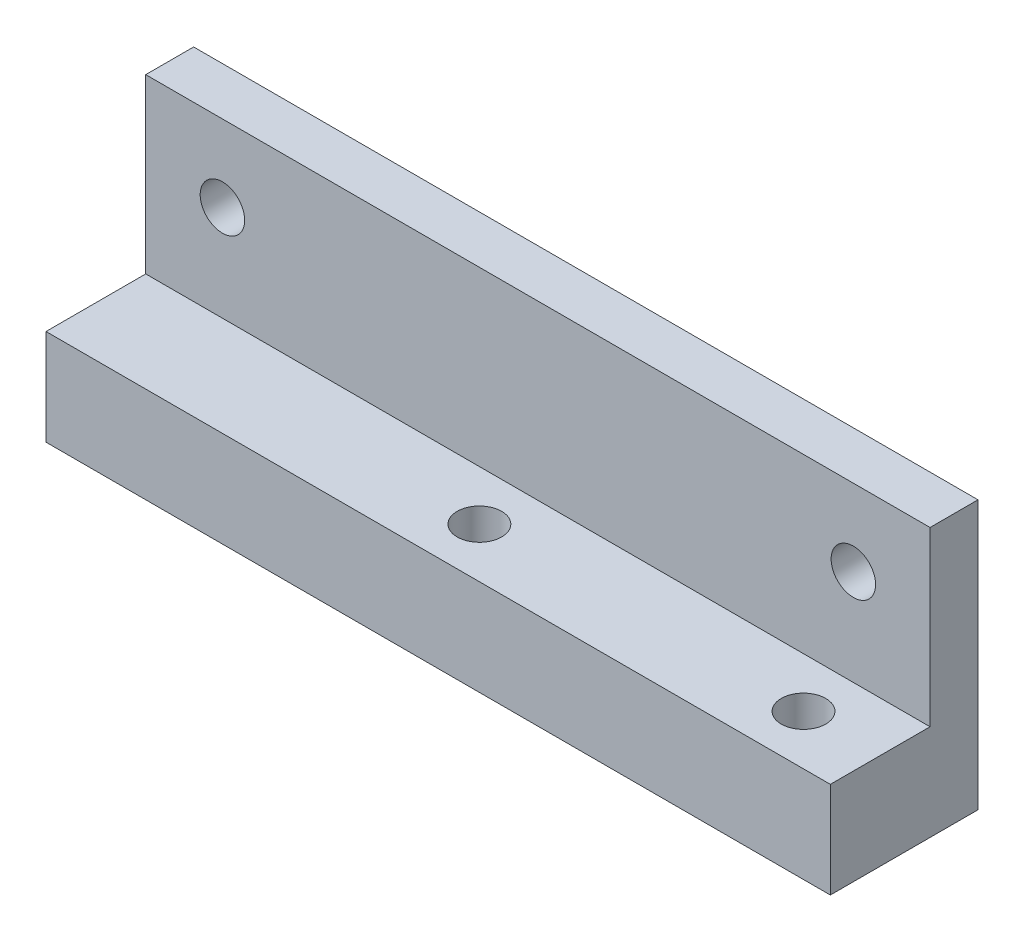
SolidWorks part; units mm, degrees
material "ABS"
ref_plane "Front Plane" through (0, 0, 0) normal (0, 0, 1) x (1, 0, 0)
ref_plane "Top Plane" through (0, 0, 0) normal (0, 1, 0) x (1, 0, 0)
ref_plane "Right Plane" through (0, 0, 0) normal (1, 0, 0) x (0, 0, -1)
sketch "Sketch1" plane through (0, 0, 0) normal (0, 1, 0) x (1, 0, 0)
  line L1 (0, 0) -> (51.943, 0)
  line L2 (0, 0) -> (0, 9.779)
  line L3 (0, 9.779) -> (51.943, 9.779)
  line L4 (51.943, 0) -> (51.943, 9.779)
  dimension "D1" = 51.943
  dimension "D2" = 9.779
extrude "Boss-Extrude1" add sketch "Sketch1" along normal blind 6.35
sketch "Sketch2" plane through (0, 6.35, 0) normal (0, 1, 0) x (1, 0, 0)
  line L1 (0, 9.779) -> (51.943, 9.779)
  line L2 (0, 9.779) -> (0, 6.604)
  line L3 (0, 6.604) -> (51.943, 6.604)
  line L4 (51.943, 9.779) -> (51.943, 6.604)
  dimension "D1" = 3.175
extrude "Boss-Extrude2" add sketch "Sketch2" along normal blind 11.43
sketch "Sketch3" plane through (0, 6.35, 0) normal (0, 1, 0) x (1, 0, 0)
  line L0 (0, 6.604) -> (0, 0) construction
  line L1 (51.943, 0) -> (51.943, 6.604) construction
  circle A0 centre (25.4, 3.302) radius 1.4732
  circle A1 centre (46.863, 3.302) radius 1.4732
  point P8 (0, 3.302)
  dimension "D1" = 2.9464
  dimension "D2" = 25.4
  dimension "D3" = 5.08
sketch "Sketch4" plane through (0, 0, -6.604) normal (0, 0, 1) x (1, 0, 0)
  line L0 (0, 17.78) -> (0, 6.35) construction
  line L1 (51.943, 17.78) -> (51.943, 6.35) construction
  line L3 (0, 17.78) -> (51.943, 17.78) construction
  circle A0 centre (46.863, 12.7) radius 1.4732
  circle A1 centre (5.08, 12.7) radius 1.4732
  dimension "D3" = 2.9464
  dimension "D1" = 5.08
  dimension "D2" = 5.08
  dimension "D4" = 5.08
extrude "Cut-Extrude1" cut sketch "Sketch4" against normal blind 6.35
extrude "Cut-Extrude2" cut sketch "Sketch3" against normal blind 6.35
